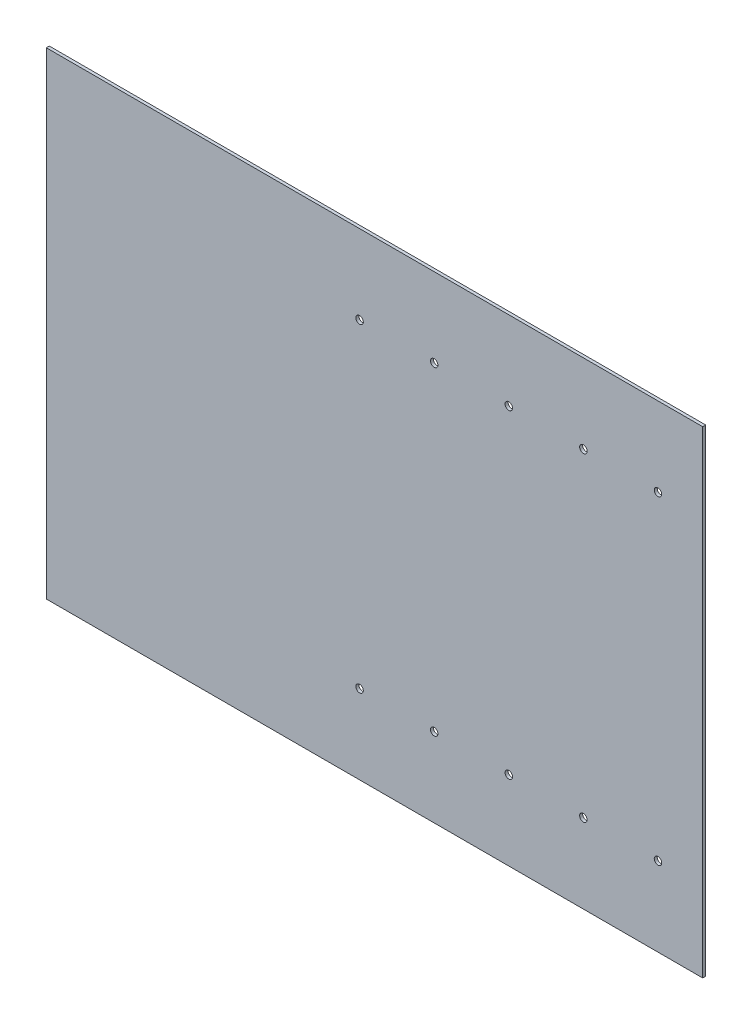
SolidWorks part; units mm, degrees
ref_plane "前视基准面" through (0, 0, 0) normal (0, 0, 1) x (1, 0, 0)
ref_plane "上视基准面" through (0, 0, 0) normal (0, 1, 0) x (1, 0, 0)
ref_plane "右视基准面" through (0, 0, 0) normal (1, 0, 0) x (0, 0, -1)
sketch "草图1" plane through (0, 0, 0) normal (0, 0, 1) x (1, 0, 0)
  line L1 (-220, 160) -> (220, 160)
  line L2 (-220, 160) -> (-220, -160)
  line L3 (-220, -160) -> (220, -160)
  line L4 (220, 160) -> (220, -160)
  line L5 (-220, 160) -> (220, -160) construction
  line L6 (-220, -160) -> (220, 160) construction
  point P0 (0, 0)
  dimension "D1" = 320
  dimension "D2" = 440
extrude "凸台-拉伸1" add sketch "草图1" along normal blind 2
sketch "草图2" plane through (0, 0, 2) normal (0, 0, 1) x (1, 0, 0)
  line L0 (220, -160) -> (220, 160) construction
  line L1 (55, 0) -> (-55, 0) construction
  circle A0 centre (190, 107) radius 2.5
  circle A1 centre (140, 107) radius 2.5
  circle A2 centre (90, 107) radius 2.5
  circle A3 centre (40, 107) radius 2.5
  circle A4 centre (-10, 107) radius 2.5
  circle A5 centre (-10, -107) radius 2.5
  circle A6 centre (40, -107) radius 2.5
  circle A7 centre (90, -107) radius 2.5
  circle A8 centre (140, -107) radius 2.5
  circle A9 centre (190, -107) radius 2.5
  dimension "D1" = 5
  dimension "D2" = 107
  dimension "D3" = 30
  dimension "D4" = 5
extrude "切除-拉伸1" cut sketch "草图2" against normal blind 10
